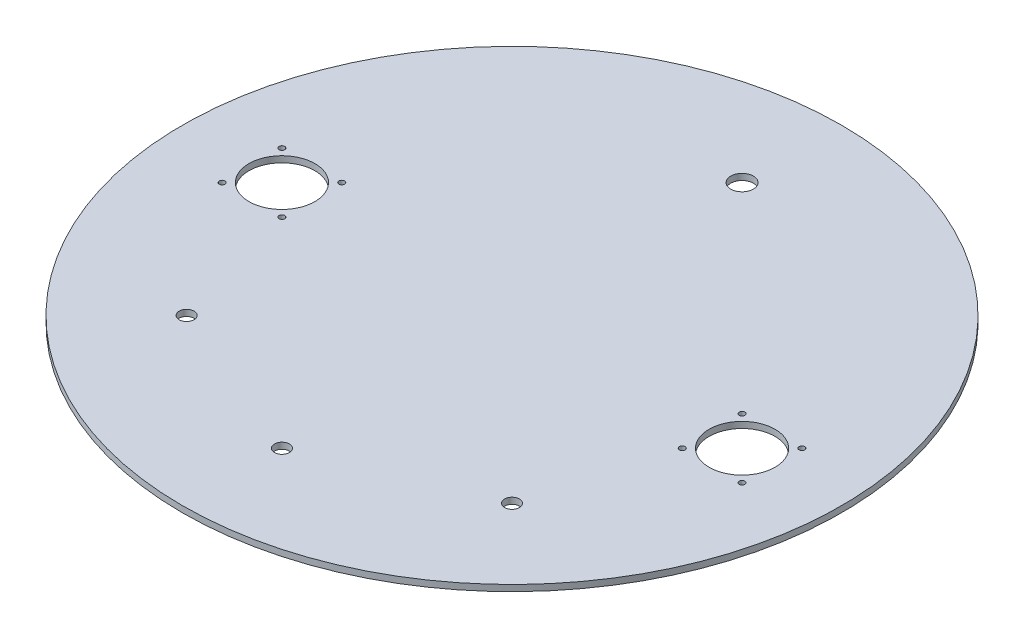
SolidWorks part; units mm, degrees
ref_plane "Front Plane" through (0, 0, 0) normal (0, 0, 1) x (1, 0, 0)
ref_plane "Top Plane" through (0, 0, 0) normal (0, 1, 0) x (1, 0, 0)
ref_plane "Right Plane" through (0, 0, 0) normal (1, 0, 0) x (0, 0, -1)
sketch "Sketch1" plane through (0, 0, 0) normal (0, 1, 0) x (1, 0, 0)
  line L0 (0, 225.0263) -> (0, -87.8934) construction
  line L1 (-185, 26.8724) -> (-185, -21.2276) construction
  line L2 (-209.05, 24.05) -> (-160.95, 24.05) construction
  line L3 (-209.05, 24.05) -> (-209.05, -24.05) construction
  line L4 (-209.05, -24.05) -> (-160.95, -24.05) construction
  line L5 (-160.95, 24.05) -> (-160.95, -24.05) construction
  line L6 (-209.05, 24.05) -> (-160.95, -24.05) construction
  line L7 (-209.05, -24.05) -> (-160.95, 24.05) construction
  line L8 (-185, 0) -> (-208.9624, 0) construction
  line L9 (-206.75, 24.05) -> (-206.75, 43.7293) construction
  line L10 (-163.25, 24.05) -> (-163.25, 43.7293) construction
  line L11 (163.25, 24.05) -> (163.25, 43.7293) construction
  line L12 (206.75, 24.05) -> (206.75, 43.7293) construction
  line L13 (185, 0) -> (208.9624, 0) construction
  line L14 (209.05, -24.05) -> (160.95, 24.05) construction
  line L15 (209.05, 24.05) -> (160.95, -24.05) construction
  line L16 (160.95, 24.05) -> (160.95, -24.05) construction
  line L17 (209.05, -24.05) -> (160.95, -24.05) construction
  line L18 (209.05, 24.05) -> (209.05, -24.05) construction
  line L19 (209.05, 24.05) -> (160.95, 24.05) construction
  line L20 (185, 26.8724) -> (185, -21.2276) construction
  line L21 (-130.8148, -130.8148) -> (0, 0) construction
  line L22 (0, 0) -> (-185, 0) construction
  line L23 (0, 0) -> (-130.8148, -130.8148) construction
  line L24 (0, 0) -> (-92.5, -160.2147) construction
  circle A0 centre (0, 0) radius 265
  circle A1 centre (-185, 0) radius 26.5
  circle A2 centre (185, 0) radius 26.5
  circle A3 centre (-209.05, 24.05) radius 2.3
  circle A4 centre (-160.95, 24.05) radius 2.3
  circle A5 centre (-160.95, -24.05) radius 2.3
  circle A6 centre (-209.05, -24.05) radius 2.3
  circle A7 centre (209.05, -24.05) radius 2.3
  circle A8 centre (160.95, -24.05) radius 2.3
  circle A9 centre (160.95, 24.05) radius 2.3
  circle A10 centre (209.05, 24.05) radius 2.3
  circle A11 centre (185, 0) radius 26.5
  circle A12 centre (0, 185) radius 9.1
  circle A13 centre (-130.8148, -130.8148) radius 6
  circle A14 centre (130.8148, -130.8148) radius 6
  circle A15 centre (-92.5, -160.2147) radius 6 [skipped]
  circle A16 centre (-47.8815, -178.6963) radius 6 [skipped]
  circle A17 centre (0, -185) radius 6
  dimension "D1" = 530
  dimension "D2" = 53
  dimension "D3" = 4.6
  dimension "D6" = 18.2
  dimension "D8" = 12
  dimension "D4" = 185
  dimension "D5" = 43.5
  dimension "D7" = 185
  dimension "D9" = 185
  dimension "D10" = 45
  dimension "D12" = 15
  dimension "D11" = 4
extrude "Boss-Extrude1" add sketch "Sketch1" along normal mid plane 5 contours A0 A10 A9 A6 A5 A2 A1 A3 A4 A7 A8 A12 A13 A14
